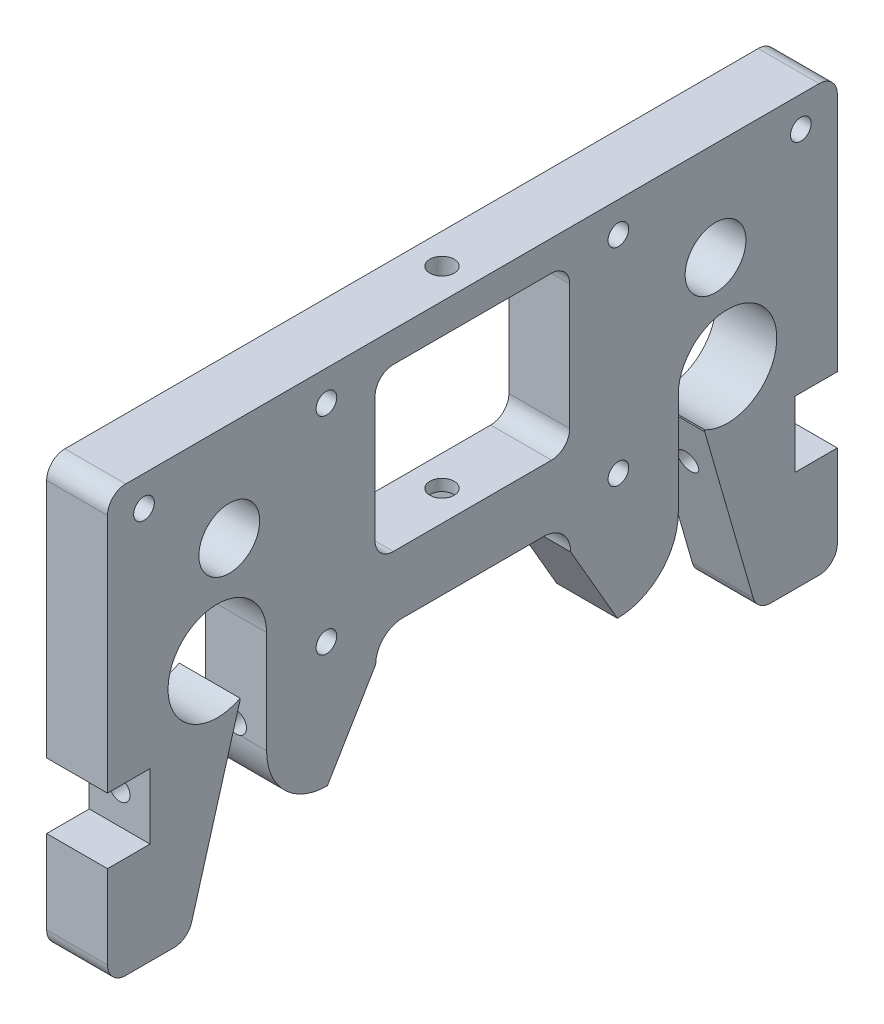
SolidWorks part; units mm, degrees
ref_plane "Спереди" through (0, 0, 0) normal (0, 0, 1) x (1, 0, 0)
ref_plane "Сверху" through (0, 0, 0) normal (0, 1, 0) x (1, 0, 0)
ref_plane "Справа" through (0, 0, 0) normal (1, 0, 0) x (0, 0, -1)
sketch "Эскиз1" plane through (0, 0, 0) normal (1, 0, 0) x (0, 0, -1)
  line L0 (3, 0) -> (10.9531, 0)
  line L1 (120, 3) -> (120, 67)
  line L2 (117, 70) -> (3, 70)
  line L3 (0, 67) -> (0, 3)
  line L4 (0, 0) -> (0, 34.4099)
  line L5 (42, 65) -> (36, 65)
  line L6 (21.8001, 29.8237) -> (13.836, 2.1698)
  line L7 (21.8001, 29.8237) -> (21.8001, 30.0903)
  line L8 (26.1553, 37.2725) -> (26.155, 20.4331)
  line L9 (60, -930) -> (60, 49070)
  line L10 (36.155, 10.433) -> (83.845, 10.433)
  line L11 (47, 65) -> (73, 65)
  line L12 (93.8447, 37.2725) -> (93.845, 20.4331)
  line L13 (36, 65) -> (36, 31)
  line L14 (36, 31) -> (36, 65)
  line L15 (98.1999, 29.8237) -> (98.1999, 30.0903)
  line L16 (47, 38.3803) -> (73, 38.3803)
  line L17 (36, 65) -> (6, 65)
  line L18 (42, 65) -> (44, 65)
  line L19 (44, 62) -> (44, 41.3803)
  line L20 (98.1999, 29.8237) -> (106.164, 2.1698)
  line L21 (76, 62) -> (76, 41.3803)
  line L22 (84, 65) -> (114, 65)
  line L23 (109.0469, 0) -> (117, 0)
  line L24 (48.5129, 23.732) -> (71.7456, 23.732) construction
  line L25 (48.5129, 28.1481) -> (71.7456, 28.1481)
  line L26 (48.5129, 19.3158) -> (71.7456, 19.3158)
  line L27 (18.0553, 37.2726) -> (18.0553, 37.321)
  arc A0 (26.1553, 37.2725) -> (21.8001, 30.0903) centre (18.0553, 37.2726) ccw
  circle A1 centre (36, 65) radius 1.7
  circle A2 centre (6, 65) radius 1.7
  circle A3 centre (36, 31) radius 1.7
  arc A4 (93.8447, 37.2725) -> (98.1999, 30.0903) centre (101.9447, 37.2726) cw
  circle A5 centre (84, 31) radius 1.7
  circle A6 centre (84, 65) radius 1.7
  circle A7 centre (114, 65) radius 1.7
  arc A8 (26.155, 20.4331) -> (36.155, 10.433) centre (36.155, 20.433) ccw
  arc A9 (93.845, 20.4331) -> (83.845, 10.433) centre (83.845, 20.433) cw
  arc A10 (44, 62) -> (47, 65) centre (47, 62) cw
  arc A11 (76, 41.3803) -> (73, 38.3803) centre (73, 41.3803) cw
  arc A12 (76, 62) -> (73, 65) centre (73, 62) ccw
  arc A13 (44, 41.3803) -> (47, 38.3803) centre (47, 41.3803) ccw
  arc A14 (3, 70) -> (0, 67) centre (3, 67) ccw
  arc A15 (120, 3) -> (117, 0) centre (117, 3) cw
  arc A16 (0, 3) -> (3, 0) centre (3, 3) ccw
  arc A17 (120, 67) -> (117, 70) centre (117, 67) ccw
  arc A18 (106.164, 2.1698) -> (109.0469, 0) centre (109.0469, 3) ccw
  arc A19 (13.836, 2.1698) -> (10.9531, 0) centre (10.9531, 3) cw
  arc A20 (48.5129, 28.1481) -> (48.5129, 19.3158) centre (48.5129, 23.732) ccw
  arc A21 (71.7456, 19.3158) -> (71.7456, 28.1481) centre (71.7456, 23.732) ccw
  point P16 (60, 70)
  point P22 (60, 10.433)
  point P36 (60, 38.3803)
  point P37 (60, 65)
  point P43 (26.1549, 10.433)
  point P46 (93.8451, 10.433)
  point P52 (76, 38.3803)
  point P55 (76, 65)
  point P58 (44, 38.3803)
  point P70 (106.7889, 0)
  point P73 (13.2111, 0)
  point P76 (60.1293, 23.732)
  dimension "D1" = 10
  dimension "D2" = 3
  dimension "D3" = 3
  dimension "D4" = 3
  dimension "D5" = 3
extrude "Бобышка-Вытянуть1" add sketch "Эскиз1" along normal blind 10
sketch "Эскиз2" plane through (0, 70, 0) normal (0, 1, 0) x (1, 0, 0)
  line L0 (5, 120) -> (5, 60)
  line L1 (10, 120) -> (0, 120) construction
  line L2 (5, 60) -> (9.6374, 60)
  circle A0 centre (5, 60) radius 2
extrude "Вырез-Вытянуть1" cut sketch "Эскиз2" against normal blind 37 contours L0 A0 L2 | L2 A0 L0
sketch "Эскиз3" plane through (0, 0, 0) normal (-1, 0, 0) x (0, 0, 1)
  line L0 (-89.4771, 22) -> (-89.4771, 24.8977)
  line L2 (-89.4771, 22) -> (-89.4771, 19.1)
  line L3 (-62.9206, 34.9875) -> (-62.9206, 36.4951)
  line L5 (-62.9206, 36.4951) -> (-57.116, 36.4951)
  line L6 (-57.116, 36.4951) -> (-57.116, 33.4799)
  line L7 (-57.116, 33.4799) -> (-62.9206, 33.4799)
  line L8 (-62.9206, 33.4799) -> (-62.9206, 35.0855)
  line L11 (-89.4771, 22) -> (-87.9771, 22)
  line L12 (-87.9771, 22) -> (-87.9771, 24.8926)
  line L13 (-87.9771, 24.8926) -> (-87.9771, 19.0972)
  line L14 (-87.9771, 19.0972) -> (-90.9771, 19.0972)
  line L15 (-90.9771, 19.0972) -> (-90.9771, 24.8926)
  line L16 (-90.9771, 24.8926) -> (-87.9771, 24.8926)
  line L18 (-32.0229, 24.8922) -> (-32.0229, 19.099)
  line L19 (-32.0229, 19.099) -> (-29.0229, 19.099)
  line L20 (-29.0229, 24.8922) -> (-32.0229, 24.8922)
  line L21 (-29.0229, 19.099) -> (-29.0229, 24.8922)
  point P14 (-60.0183, 34.9875)
  point P21 (-30.5229, 21.9956)
extrude "Вырез-Вытянуть2" cut sketch "Эскиз3" against normal blind 8
sketch "Эскиз5" plane through (0, 0, -120) normal (0, 0, -1) x (-1, 0, 0)
  line L0 (-5, 70) -> (-5, 22)
  line L1 (-10, 70) -> (0, 70) construction
  circle A0 centre (-5, 22) radius 1.7
extrude "Вырез-Вытянуть3" cut sketch "Эскиз5" against normal blind 35
sketch "Эскиз6" plane through (0, 0, 0) normal (0, 0, 1) x (1, 0, 0)
  line L0 (5, 70) -> (5, 22)
  line L1 (10, 70) -> (0, 70) construction
  circle A0 centre (5, 22) radius 1.7
extrude "Вырез-Вытянуть4" cut sketch "Эскиз6" against normal blind 35
sketch "Эскиз7" plane through (0, 0, 0) normal (-1, 0, 0) x (0, 0, 1)
  line L0 (-76.1617, 23.732) -> (-83.845, 10.433)
  line L1 (-83.845, 10.433) -> (-36.155, 10.433)
  line L2 (-36.155, 10.433) -> (-44.0968, 23.732)
  line L3 (-76.1617, 23.732) -> (-44.0968, 23.732)
  arc A0 (-71.7456, 28.1481) -> (-71.7456, 19.3158) centre (-71.7456, 23.732) ccw construction
  arc A1 (-48.5129, 19.3158) -> (-48.5129, 28.1481) centre (-48.5129, 23.732) ccw construction
extrude "Вырез-Вытянуть5" cut sketch "Эскиз7" against normal blind 10
sketch "Эскиз9" plane through (0, 0, 0) normal (-1, 0, 0) x (0, 0, 1)
  line L0 (-60, 70) -> (-60, 31.9679)
  line L1 (-117, 70) -> (-3, 70) construction
  circle A0 centre (-99.974, 53.7494) radius 5
  circle A1 centre (-20.026, 53.7494) radius 5
extrude "Вырез-Вытянуть6" cut sketch "Эскиз9" against normal blind 10 contours A0 | A1
sketch "Эскиз10" plane through (0, 0, 0) normal (0, 0, 1) x (1, 0, 0)
  line L0 (0, 67) -> (0, 3) construction
  line L1 (0, 27.4709) -> (10, 27.4709)
  line L2 (0, 27.4709) -> (0, 16.715)
  line L3 (0, 16.715) -> (10, 16.715)
  line L4 (10, 27.4709) -> (10, 16.715)
  line L5 (10, 67) -> (10, 3) construction
extrude "Вырез-Вытянуть7" cut sketch "Эскиз10" against normal blind 7
sketch "Эскиз13" plane through (0, 0, -120) normal (0, 0, -1) x (-1, 0, 0)
  line L1 (-10.2377, 16.6215) -> (0, 16.6215)
  line L2 (-10.2377, 16.6215) -> (-10.2377, 27.4709)
  line L3 (-10.2377, 27.4709) -> (0, 27.4709)
  line L4 (0, 16.6215) -> (0, 27.4709)
extrude "Вырез-Вытянуть8" cut sketch "Эскиз13" against normal blind 7
